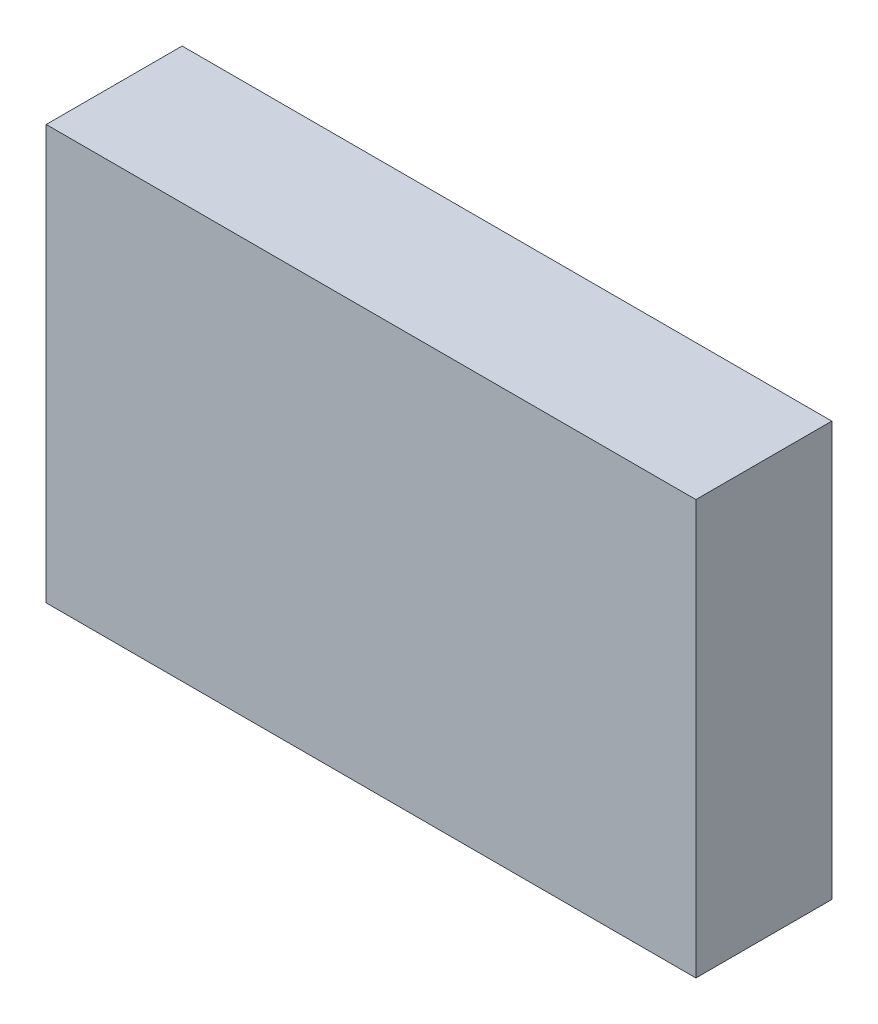
SolidWorks part; units mm, degrees
ref_plane "Plano frontal" through (0, 0, 0) normal (0, 0, 1) x (1, 0, 0)
ref_plane "Plano superior" through (0, 0, 0) normal (0, 1, 0) x (1, 0, 0)
ref_plane "Plano direito" through (0, 0, 0) normal (1, 0, 0) x (0, 0, -1)
sketch "Esboço1" plane through (0, 0, 0) normal (0, 0, 1) x (1, 0, 0)
  line L1 (-21.7668, -15.2434) -> (-19.8068, -15.2434)
  line L2 (-21.7668, -15.2434) -> (-21.7668, -16.4934)
  line L3 (-21.7668, -16.4934) -> (-19.8068, -16.4934)
  line L4 (-19.8068, -15.2434) -> (-19.8068, -16.4934)
  dimension "D1" = 1.96
  dimension "D2" = 1.25
extrude "Ressalto-extrusão1" add sketch "Esboço1" along normal blind 0.41
